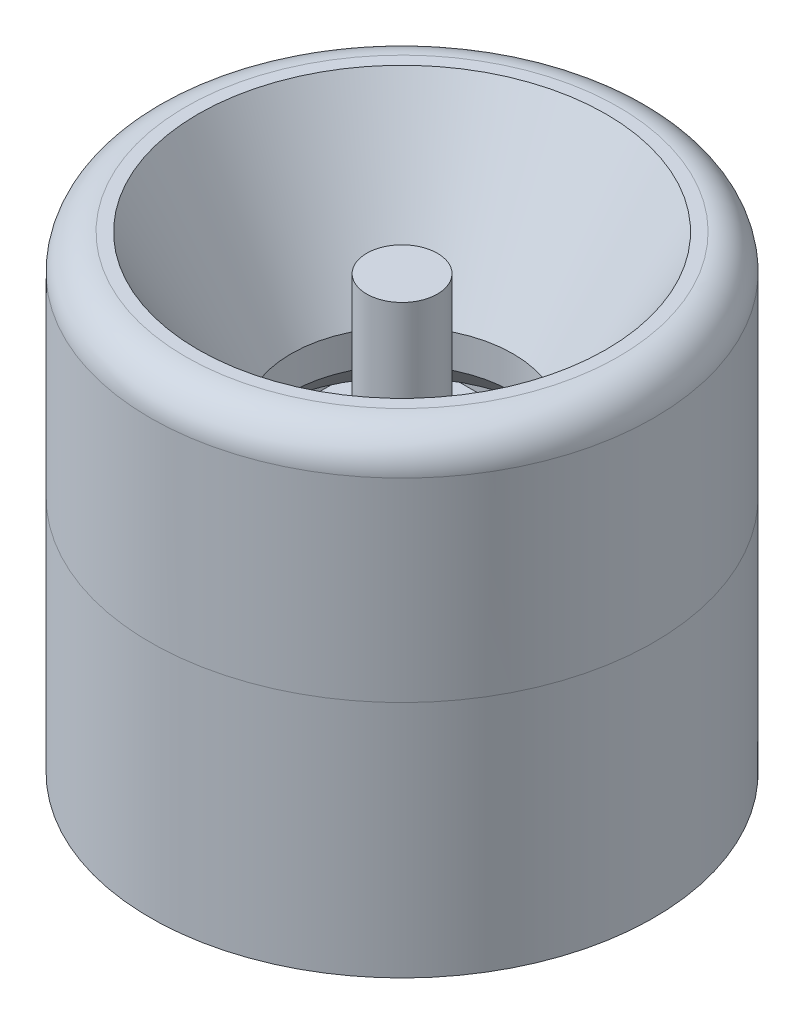
SolidWorks part; units mm, degrees
ref_plane "前视基准面" through (0, 0, 0) normal (0, 0, 1) x (1, 0, 0)
ref_plane "上视基准面" through (0, 0, 0) normal (0, 1, 0) x (1, 0, 0)
ref_plane "右视基准面" through (0, 0, 0) normal (1, 0, 0) x (0, 0, -1)
sketch "草图1" plane through (0, 0, 0) normal (0, 1, 0) x (1, 0, 0)
  line L1 (-8, -7.65) -> (8.5, -7.65)
  line L2 (-8, -7.65) -> (-8, 7.75)
  line L3 (-8, 7.75) -> (8.5, 7.75)
  line L4 (8.5, -7.65) -> (8.5, 7.75)
  circle A0 centre (0, 0) radius 0.5
  dimension "D5" = 1
  dimension "D1" = 16.5
  dimension "D2" = 15.4
  dimension "D3" = 8
  dimension "D4" = 7.65
extrude "凸台-拉伸1" add sketch "草图1" along normal blind 7.5
sketch "草图2" plane through (0, 0, 0) normal (0, -1, 0) x (1, 0, 0)
  line L1 (8.5, 7.65) -> (-3.5, 7.65)
  line L2 (8.5, 7.65) -> (8.5, 10.35)
  line L3 (8.5, 10.35) -> (-3.5, 10.35)
  line L4 (-3.5, 7.65) -> (-3.5, 10.35)
  dimension "D1" = 12
  dimension "D2" = 2.7
extrude "凸台-拉伸2" add sketch "草图2" against normal blind 2
sketch "草图3" plane through (0, 2, 0) normal (0, 1, 0) x (1, 0, 0)
  line L0 (8.5, -7.65) -> (8.5, -10.35) construction
  line L1 (-3.5, -10.35) -> (8.5, -10.35)
  line L2 (-3.5, -10.35) -> (-3.5, -9.85)
  line L3 (-3.5, -9.85) -> (8.5, -9.85)
  line L4 (8.5, -10.35) -> (8.5, -9.85)
  dimension "D1" = 0.5
extrude "凸台-拉伸3" add sketch "草图3" against normal blind 6
sketch "草图4" plane through (0, 7.5, 0) normal (0, 1, 0) x (1, 0, 0)
  circle A0 centre (0, 0) radius 0.5 construction
  circle A1 centre (0, 0) radius 0.5 construction
  circle A2 centre (0, 0) radius 2
  dimension "D1" = 4
extrude "凸台-拉伸4" add sketch "草图4" along normal blind 11.45
sketch "草图5" plane through (0, 0, 0) normal (0, 0, 1) x (1, 0, 0)
  line L0 (0, 0) -> (0, 12.5288) construction
  line L1 (0, 9) -> (5.1371, 9)
  line L2 (0, 5.9) -> (6, 5.9)
  line L3 (-8, 0) -> (-3.5, 0) construction
  line L4 (0, 9) -> (0, 5.9)
  arc A0 (5.1371, 9) -> (6, 5.9) centre (0, 5.9) cw
  dimension "D3" = 6
  dimension "D1" = 5.9
  dimension "D2" = 9
revolve "旋转1" add sketch "草图5" angle 360 about L0
sketch "草图6" plane through (0, 0, 0) normal (0, -1, 0) x (1, 0, 0)
  line L0 (-8.2, 7.85) -> (-8.2, -7.95)
  line L1 (-8.2, -7.95) -> (8.7, -7.95)
  line L2 (8.7, -7.95) -> (8.7, 7.85)
  line L3 (8.7, 7.85) -> (-8.2, 7.85)
  line L4 (-8, 7.65) -> (-8, -7.75)
  line L5 (8.5, 7.65) -> (-8, 7.65)
  line L6 (8.5, -7.75) -> (8.5, 7.65)
  line L7 (-8, -7.75) -> (8.5, -7.75)
  line L8 (-8, 7.65) -> (-8, -7.75) construction
  line L9 (8.5, 7.65) -> (-8, 7.65) construction
  line L10 (8.5, -7.75) -> (8.5, 7.65) construction
  line L11 (-8, -7.75) -> (8.5, -7.75) construction
  circle A0 centre (0, 0) radius 14.25
  dimension "D3" = 28.5
  dimension "D1" = 0
  dimension "D2" = 0.2
extrude "凸台-拉伸5" add sketch "草图6" against normal blind 8 separate body
sketch "草图8" plane through (0, 0, 0) normal (0, -1, 0) x (1, 0, 0)
  line L6 (8.7, 7.85) -> (-8.2, 7.85)
  line L7 (8.7, -7.95) -> (8.7, 7.85)
  line L8 (-8.2, -7.95) -> (8.7, -7.95)
  line L9 (-8.2, 7.85) -> (-8.2, -7.95)
  line L10 (8.7, 7.85) -> (-8.2, 7.85) construction
  line L11 (8.7, -7.95) -> (8.7, 7.85) construction
  line L12 (-8.2, -7.95) -> (8.7, -7.95) construction
  line L13 (-8.2, 7.85) -> (-8.2, -7.95) construction
  circle A1 centre (0, 0) radius 14.25
  circle A2 centre (0, 0) radius 14.25
  dimension "D1" = 0
  dimension "D2" = 0
extrude "凸台-拉伸6" add sketch "草图8" along normal blind 5.5
sketch "草图7" plane through (0, 8, 0) normal (0, -1, 0) x (1, 0, 0)
  line L1 (-4.3, 7.85) -> (8.7, 7.85)
  line L2 (-4.3, 7.85) -> (-4.3, 10.45)
  line L3 (-4.3, 10.45) -> (8.7, 10.45)
  line L4 (8.7, 7.85) -> (8.7, 10.45)
  line L6 (8.7, 7.85) -> (-8.2, 7.85) construction
  line L7 (8.7, -7.95) -> (8.7, 7.85) construction
  dimension "D1" = 2.6
  dimension "D2" = 13
extrude "切除-拉伸2" cut sketch "草图7" along normal blind 13
fillet "圆角1" radius 0.5 1 edges at (8.7, 1.5, 10.45)
sketch "草图9" plane through (0, -5.5, 0) normal (0, -1, 0) x (1, 0, 0)
  line L0 (0, 0) -> (0, 9.0675) construction
  line L1 (0, 0) -> (11, 0) construction
  circle A0 centre (11, 0) radius 1.65
  circle A1 centre (-11, 0) radius 1.65
  dimension "D1" = 3.3
  dimension "D2" = 22
extrude "切除-拉伸3" cut sketch "草图9" against normal blind 7
sketch "草图10" plane through (0, -5.5, 0) normal (0, -1, 0) x (1, 0, 0)
  circle A0 centre (0, 0) radius 2.9
  dimension "D1" = 5.8
extrude "凸台-拉伸7" [suppressed] add sketch "草图10" along normal blind 1
sketch "草图11" plane through (0, 8, 0) normal (0, 1, 0) x (1, 0, 0)
  line L0 (0, 0) -> (0, 16.0679) construction
  line L1 (0, 0) -> (11.3, 0) construction
  line L2 (-10.05, -3.5) -> (-10.05, 3.5)
  line L3 (10.05, -3.5) -> (12.55, -3.5)
  line L4 (10.05, -3.5) -> (10.05, 3.5)
  line L5 (10.05, 3.5) -> (12.55, 3.5)
  line L6 (12.55, -3.5) -> (12.55, 3.5)
  line L7 (10.05, -3.5) -> (12.55, 3.5) construction
  line L8 (10.05, 3.5) -> (12.55, -3.5) construction
  line L9 (-10.05, -3.5) -> (-12.55, -3.5)
  line L10 (-12.55, -3.5) -> (-12.55, 3.5)
  line L11 (-10.05, 3.5) -> (-12.55, 3.5)
  line L13 (-3.5, 12.55) -> (3.5, 12.55)
  line L14 (-3.5, 12.55) -> (-3.5, 10.05)
  line L15 (-3.5, 10.05) -> (3.5, 10.05)
  line L16 (3.5, 12.55) -> (3.5, 10.05)
  line L17 (-3.5, 12.55) -> (3.5, 10.05) construction
  line L18 (-3.5, 10.05) -> (3.5, 12.55) construction
  point P8 (0, 11.3)
  dimension "D1" = 2.5
  dimension "D2" = 7
  dimension "D3" = 11.3
  dimension "D4" = 11.3
extrude "切除-拉伸4" cut sketch "草图11" against normal blind 5
sketch "草图12" plane through (0, 0, 0) normal (0, 1, 0) x (1, 0, 0)
  line L1 (8.7, 0.05) -> (7.95, 0.05) construction
  line L2 (8.7, 7.95) -> (8.7, -7.85) construction
  line L3 (0.25, 7.95) -> (0.25, 7.2) construction
  line L4 (7.2, -1.95) -> (8.7, -1.95)
  line L5 (7.2, -1.95) -> (7.2, 2.05)
  line L6 (7.2, 2.05) -> (8.7, 2.05)
  line L7 (8.7, -1.95) -> (8.7, 2.05)
  line L8 (7.2, -1.95) -> (8.7, 2.05) construction
  line L9 (7.2, 2.05) -> (8.7, -1.95) construction
  line L10 (-8.2, 7.95) -> (8.7, 7.95) construction
  line L11 (-8.2, 0.05) -> (-7.45, 0.05) construction
  line L12 (-1.75, 6.45) -> (2.25, 6.45)
  line L13 (-1.75, 6.45) -> (-1.75, 7.95)
  line L14 (-1.75, 7.95) -> (2.25, 7.95)
  line L15 (2.25, 6.45) -> (2.25, 7.95)
  line L16 (-1.75, 6.45) -> (2.25, 7.95) construction
  line L17 (-1.75, 7.95) -> (2.25, 6.45) construction
  line L18 (-8.2, -7.85) -> (-8.2, 7.95) construction
  line L19 (-8.2, -7.85) -> (-8.2, 7.95) construction
  line L20 (-6.7, -1.95) -> (-8.2, -1.95)
  line L21 (-6.7, -1.95) -> (-6.7, 2.05)
  line L22 (-6.7, 2.05) -> (-8.2, 2.05)
  line L23 (-8.2, -1.95) -> (-8.2, 2.05)
  line L24 (-6.7, -1.95) -> (-8.2, 2.05) construction
  line L25 (-6.7, 2.05) -> (-8.2, -1.95) construction
  dimension "D1" = 4
  dimension "D2" = 1.5
extrude "切除-拉伸5" cut sketch "草图12" against normal blind 7
sketch "草图13" plane through (0, 8, 0) normal (0, 1, 0) x (1, 0, 0)
  circle A1 centre (0, 0) radius 14.25
  circle A2 centre (0, 0) radius 14.25
  dimension "D1" = 0
extrude "凸台-拉伸8" add sketch "草图13" along normal blind 13 separate body
sketch "草图14" plane through (0, 0, 0) normal (0, 0, 1) x (1, 0, 0)
  line L0 (14.25, 8) -> (-14.25, 8) construction
  line L1 (14.25, 8) -> (-14.25, 8) construction
  line L2 (5.1371, 9) -> (-5.1371, 9) construction
  line L3 (5.1371, 9) -> (-5.1371, 9) construction
  line L4 (0, 1) -> (0, 24.7898) construction
  line L5 (0, 1) -> (13.7351, 24.7898)
  line L6 (0, 24.7898) -> (13.7351, 24.7898)
  line L7 (0, 24.7898) -> (0, 1)
  dimension "D1" = 30
  dimension "D2" = 8
revolve "切除-旋转1" cut sketch "草图14" angle 360 about L7
sketch "草图15" plane through (0, 8, 0) normal (0, -1, 0) x (1, 0, 0)
  circle A0 centre (0, 0) radius 5.7827 construction
  circle A1 centre (0, 0) radius 5.7827 construction
  circle A2 centre (0, 0) radius 6.2827
  dimension "D1" = 0.5
extrude "切除-拉伸6" cut sketch "草图15" against normal blind 15
fillet "圆角2" radius 2 1 edges at (0, 21, 14.25)
sketch "草图16" plane through (0, 8, 0) normal (0, -1, 0) x (1, 0, 0)
  line L0 (-10.17, 3.38) -> (-12.43, 3.38)
  line L1 (-12.43, 3.38) -> (-12.43, -3.38)
  line L2 (-12.43, -3.38) -> (-10.17, -3.38)
  line L3 (-10.17, -3.38) -> (-10.17, 3.38)
  line L4 (-10.05, 3.5) -> (-12.55, 3.5)
  line L5 (-10.05, -3.5) -> (-10.05, 3.5)
  line L6 (-12.55, -3.5) -> (-10.05, -3.5)
  line L7 (-12.55, 3.5) -> (-12.55, -3.5)
  line L8 (-10.05, 3.5) -> (-12.55, 3.5) construction
  line L9 (-10.05, -3.5) -> (-10.05, 3.5) construction
  line L10 (-12.55, -3.5) -> (-10.05, -3.5) construction
  line L11 (-12.55, 3.5) -> (-12.55, -3.5) construction
  line L12 (12.55, -3.5) -> (12.55, 3.5)
  line L13 (10.05, -3.5) -> (12.55, -3.5)
  line L14 (10.05, 3.5) -> (10.05, -3.5)
  line L15 (12.55, 3.5) -> (10.05, 3.5)
  line L16 (12.55, -3.5) -> (12.55, 3.5) construction
  line L17 (10.05, -3.5) -> (12.55, -3.5) construction
  line L18 (10.05, 3.5) -> (10.05, -3.5) construction
  line L19 (12.55, 3.5) -> (10.05, 3.5) construction
  line L20 (12.43, -3.38) -> (12.43, 3.38)
  line L21 (12.43, 3.38) -> (10.17, 3.38)
  line L22 (10.17, 3.38) -> (10.17, -3.38)
  line L23 (10.17, -3.38) -> (12.43, -3.38)
  line L24 (3.38, -12.43) -> (3.38, -10.17)
  line L25 (3.38, -10.17) -> (-3.38, -10.17)
  line L26 (-3.38, -10.17) -> (-3.38, -12.43)
  line L27 (-3.38, -12.43) -> (3.38, -12.43)
  line L28 (3.5, -12.55) -> (3.5, -10.05)
  line L29 (-3.5, -12.55) -> (3.5, -12.55)
  line L30 (-3.5, -10.05) -> (-3.5, -12.55)
  line L31 (3.5, -10.05) -> (-3.5, -10.05)
  line L32 (3.5, -12.55) -> (3.5, -10.05) construction
  line L33 (-3.5, -12.55) -> (3.5, -12.55) construction
  line L34 (-3.5, -10.05) -> (-3.5, -12.55) construction
  line L35 (3.5, -10.05) -> (-3.5, -10.05) construction
  dimension "D1" = 0
  dimension "D2" = 0
  dimension "D3" = 0.12
  dimension "D4" = 0
  dimension "D5" = 0.12
extrude "凸台-拉伸9" add sketch "草图16" along normal blind 4
fillet "圆角3" radius 0.8 12 edges at (12.43, 6, 3.38) (10.17, 6, 3.38) (10.17, 6, -3.38) (12.43, 6, -3.38) (3.38, 6, -12.43) (3.38, 6, -10.17) (-3.38, 6, -10.17) (-3.38, 6, -12.43) (-10.17, 6, 3.38) (-12.43, 6, 3.38) (-10.17, 6, -3.38) (-12.43, 6, -3.38)
sketch "草图17" plane through (0, -5.5, 0) normal (0, -1, 0) x (1, 0, 0)
  circle A0 centre (0, 0) radius 4
  dimension "D1" = 8
extrude "切除-拉伸7" cut sketch "草图17" against normal up to surface (13.5 mm away) up to face at (11.3, 8, 0)
sketch "草图18" plane through (0, -5.5, 0) normal (0, -1, 0) x (1, 0, 0)
  line L0 (-2.1678, 5.999) -> (5.989, 2.1955) construction
  line L1 (-2.1678, 5.999) -> (5.989, 2.1955)
chamfer "倒角1" distance 2 angle 45 1 edges at (0, 8, -6.2827)
equation "\"D4@草图11\"=\"D3@草图11\""
